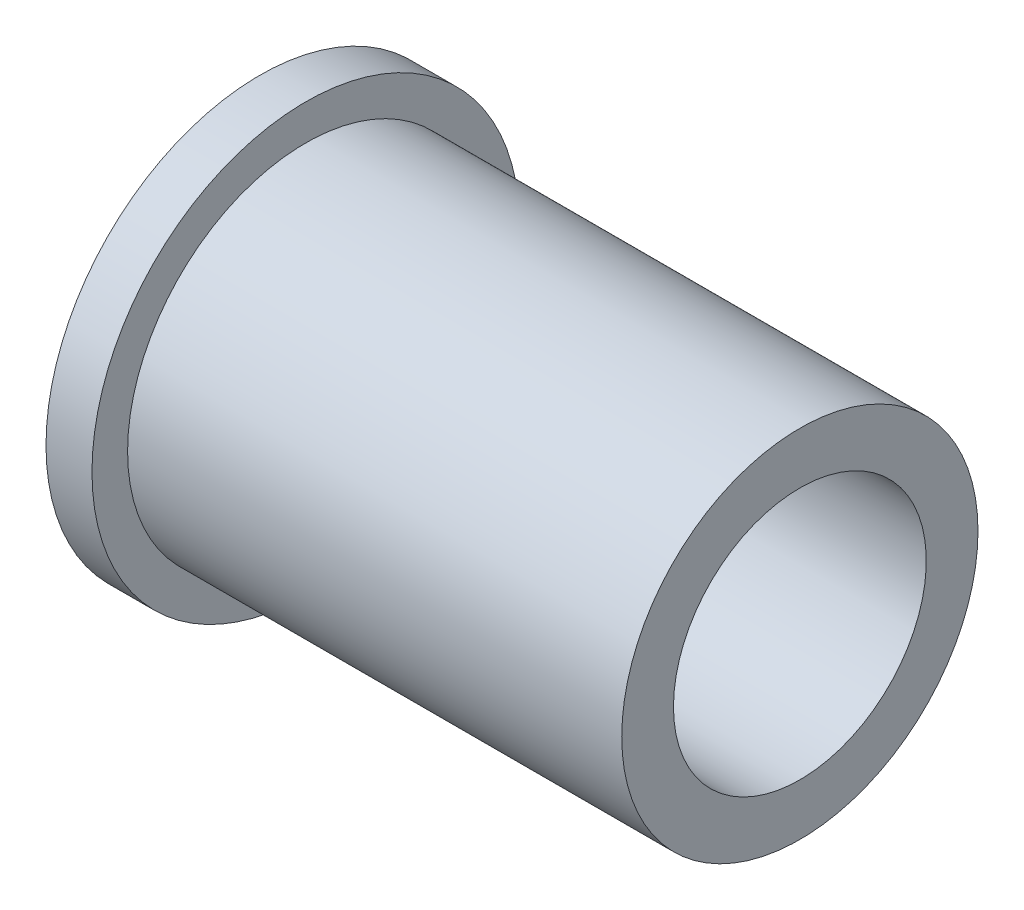
SolidWorks part; units mm, degrees
ref_plane "Plan de face" through (0, 0, 0) normal (0, 0, 1) x (1, 0, 0)
ref_plane "Plan de dessus" through (0, 0, 0) normal (0, 1, 0) x (1, 0, 0)
ref_plane "Plan de droite" through (0, 0, 0) normal (1, 0, 0) x (0, 0, -1)
sketch "Esquisse1" plane through (0, 0, 0) normal (0, 0, 1) x (1, 0, 0)
  line L0 (0, 0) -> (109.3704, 0) construction
  line L1 (0, 18.6) -> (0, 11)
  line L2 (0, 11) -> (47, 11)
  line L3 (47, 11) -> (47, 15.5)
  line L4 (47, 15.5) -> (4, 15.5)
  line L5 (4, 15.5) -> (4, 18.6)
  line L6 (4, 18.6) -> (0, 18.6)
  dimension "D1" = 11
  dimension "D2" = 15.5
  dimension "D3" = 18.6
  dimension "D4" = 47
  dimension "D5" = 4
revolve "Révolution1" add sketch "Esquisse1" angle 360 about L0
